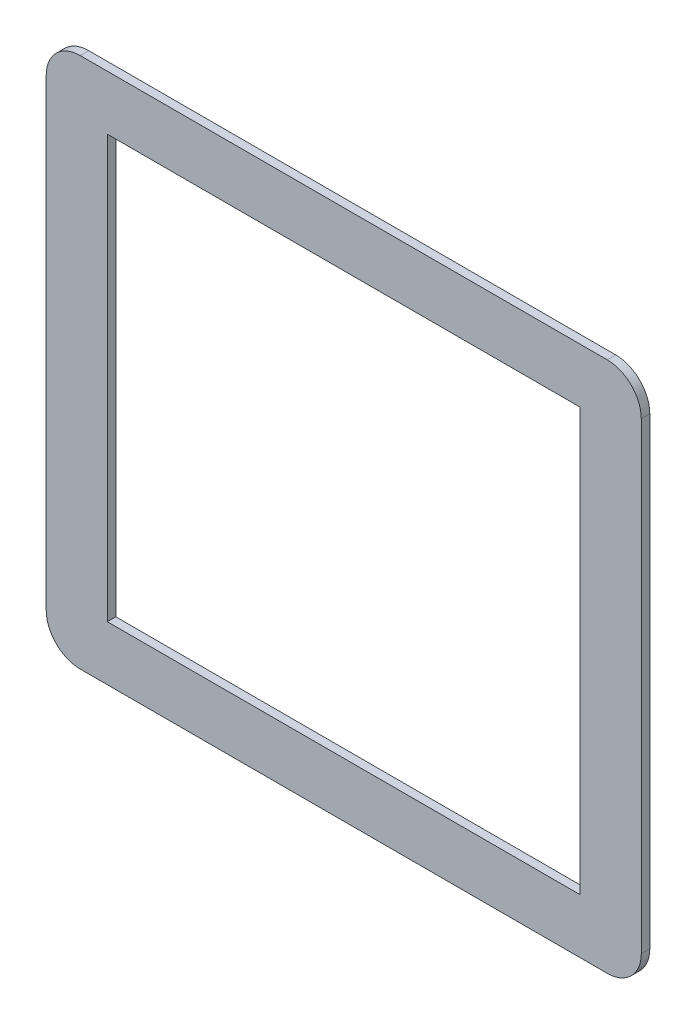
SolidWorks part; units mm, degrees
material "Plain Carbon Steel"
ref_plane "Front Plane" through (0, 0, 0) normal (0, 0, 1) x (1, 0, 0)
ref_plane "Top Plane" through (0, 0, 0) normal (0, 1, 0) x (1, 0, 0)
ref_plane "Right Plane" through (0, 0, 0) normal (1, 0, 0) x (0, 0, -1)
sketch "Sketch1" plane through (0, 0, 0) normal (0, 0, 1) x (1, 0, 0)
  line L0 (-111.2515, 99.3317) -> (111.2515, 99.3317)
  line L1 (-124, 125) -> (124, 125)
  line L2 (-140, 109) -> (-140, -109)
  line L3 (-124, -125) -> (124, -125)
  line L4 (140, 109) -> (140, -109)
  line L5 (-140, 125) -> (140, -125) construction
  line L6 (-140, -125) -> (140, 125) construction
  line L7 (111.2515, 99.3317) -> (111.2515, -99.3317)
  line L8 (111.2515, -99.3317) -> (-111.2515, -99.3317)
  line L9 (-111.2515, -99.3317) -> (-111.2515, 99.3317)
  arc A0 (-140, -109) -> (-124, -125) centre (-124, -109) ccw
  arc A1 (124, -125) -> (140, -109) centre (124, -109) ccw
  arc A2 (124, 125) -> (140, 109) centre (124, 109) cw
  arc A3 (-124, 125) -> (-140, 109) centre (-124, 109) ccw
  circle A4 centre (-124, 109) radius 16 construction
  point P0 (0, 0)
  point P19 (-111.2515, 99.3317)
  dimension "D3" = 16
  dimension "D1" = 280
  dimension "D2" = 250
extrude "Boss-Extrude1" add sketch "Sketch1" along normal blind 4
